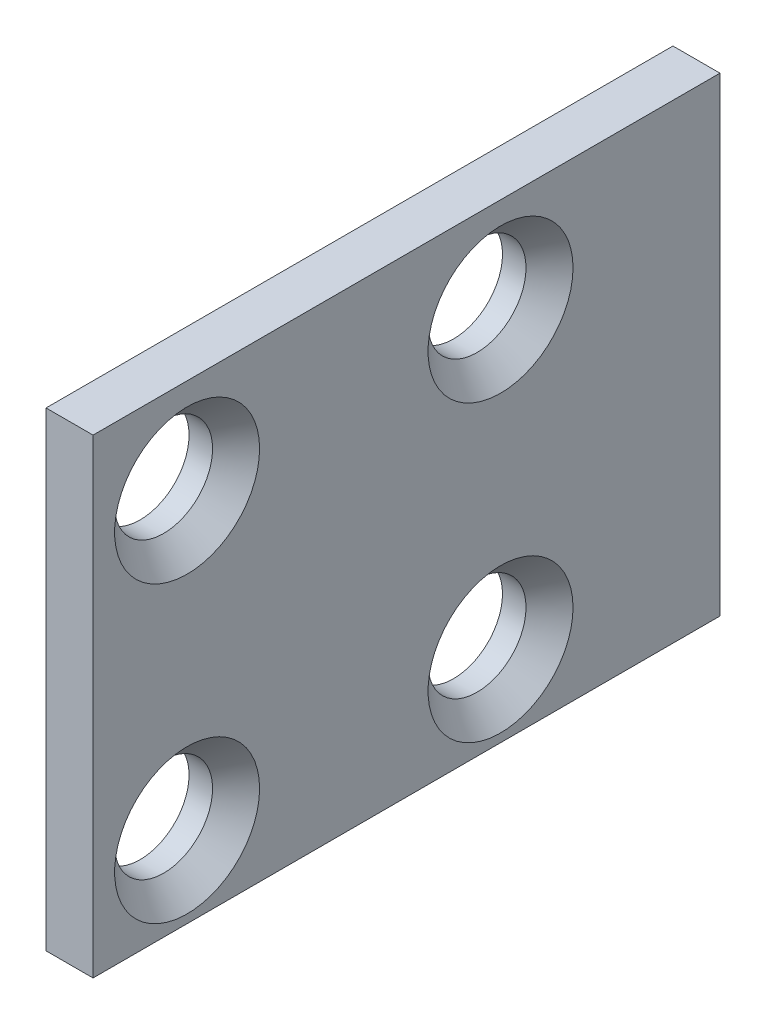
SolidWorks part; units mm, degrees
material "AISI 1045 Aço, trefilado"
ref_plane "Plano frontal" through (0, 0, 0) normal (0, 0, 1) x (1, 0, 0)
ref_plane "Plano superior" through (0, 0, 0) normal (0, 1, 0) x (1, 0, 0)
ref_plane "Plano direito" through (0, 0, 0) normal (1, 0, 0) x (0, 0, -1)
sketch "Esboço1" plane through (0, 0, 0) normal (1, 0, 0) x (0, 0, -1)
  line L0 (0, 0) -> (80, 0)
  line L1 (80, 0) -> (80, 60)
  line L2 (80, 60) -> (0, 60)
  line L3 (0, 60) -> (0, 0)
  circle A0 centre (12, 10.3277) radius 6.25
  circle A1 centre (12, 47.8722) radius 6.25
  circle A2 centre (52, 47.8722) radius 6.25
  circle A3 centre (52, 10.3277) radius 6.25
extrude "Ressalto-extrusão1" add sketch "Esboço1" along normal blind 6
chamfer "Chanfro1" distance 3 angle 45 4 edges at (6, 10.3277, -18.25) (6, 10.3277, -58.25) (6, 47.8722, -58.25) (6, 47.8722, -18.25)
